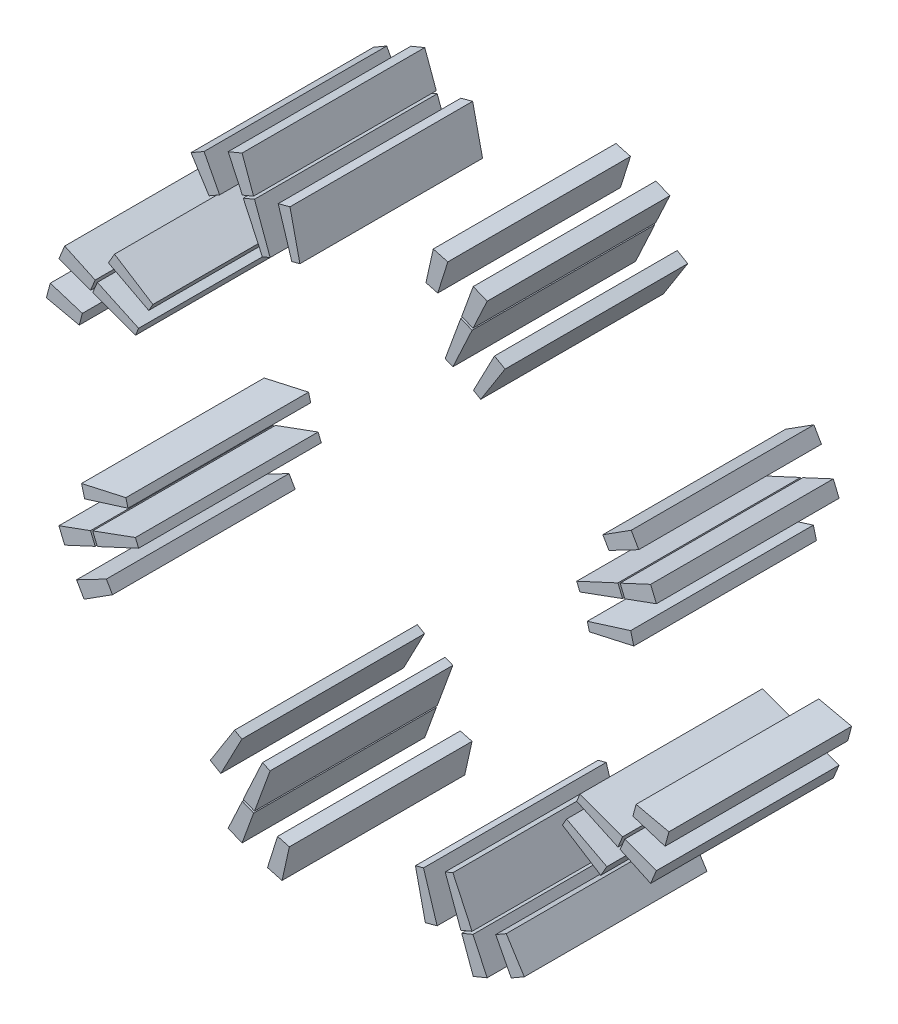
SolidWorks part; units mm, degrees
ref_plane "Спереди" through (0, 0, 0) normal (0, 0, 1) x (1, 0, 0)
ref_plane "Сверху" through (0, 0, 0) normal (0, 1, 0) x (1, 0, 0)
ref_plane "Справа" through (0, 0, 0) normal (1, 0, 0) x (0, 0, -1)
sketch "Эскиз1" plane through (0, 0, 0) normal (0, 0, 1) x (1, 0, 0)
  line L0 (38.0587, 9.486) -> (45.3455, 11.1141)
  line L1 (45.3455, 11.1141) -> (44.8274, 13.0476)
  line L2 (44.8274, 13.0476) -> (37.7028, 10.8142)
  line L3 (37.7028, 10.8142) -> (38.0587, 9.486)
  line L4 (43.8666, 17.0868) -> (49.0554, 18.98)
  line L5 (49.0554, 18.98) -> (48.1083, 21.2666)
  line L6 (48.1083, 21.2666) -> (43.1006, 18.9361)
  line L7 (43.1006, 18.9361) -> (43.8666, 17.0868)
  line L8 (36.4949, 14.3725) -> (43.5069, 16.9378)
  line L9 (43.5069, 16.9378) -> (42.7409, 18.7871)
  line L10 (42.7409, 18.7871) -> (35.9687, 15.6429)
  line L11 (35.9687, 15.6429) -> (36.4949, 14.3725)
  line L12 (41.261, 22.6664) -> (46.1584, 25.2206)
  line L13 (46.1584, 25.2206) -> (44.9209, 27.364)
  line L14 (44.9209, 27.364) -> (40.2602, 24.3999)
  line L15 (40.2602, 24.3999) -> (41.261, 22.6664)
  line L16 (20.2039, 33.6192) -> (24.2052, 39.923)
  line L17 (24.2052, 39.923) -> (22.4717, 40.9238)
  line L18 (22.4717, 40.9238) -> (19.0131, 34.3067)
  line L19 (19.0131, 34.3067) -> (20.2039, 33.6192)
  line L20 (18.9361, 43.1006) -> (21.2666, 48.1083)
  line L21 (21.2666, 48.1083) -> (18.98, 49.0554)
  line L22 (18.98, 49.0554) -> (17.0868, 43.8666)
  line L23 (17.0868, 43.8666) -> (18.9361, 43.1006)
  line L24 (15.6429, 35.9687) -> (18.7871, 42.7409)
  line L25 (18.7871, 42.7409) -> (16.9378, 43.5069)
  line L26 (16.9378, 43.5069) -> (14.3725, 36.4949)
  line L27 (14.3725, 36.4949) -> (15.6429, 35.9687)
  line L28 (13.1484, 45.2035) -> (14.8052, 50.4725)
  line L29 (14.8052, 50.4725) -> (12.4146, 51.1131)
  line L30 (12.4146, 51.1131) -> (11.2149, 45.7216)
  line L31 (11.2149, 45.7216) -> (13.1484, 45.2035)
  line L32 (-9.486, 38.0587) -> (-11.1141, 45.3455)
  line L33 (-11.1141, 45.3455) -> (-13.0476, 44.8274)
  line L34 (-13.0476, 44.8274) -> (-10.8142, 37.7028)
  line L35 (-10.8142, 37.7028) -> (-9.486, 38.0587)
  line L36 (-17.0868, 43.8666) -> (-18.98, 49.0554)
  line L37 (-18.98, 49.0554) -> (-21.2666, 48.1083)
  line L38 (-21.2666, 48.1083) -> (-18.9361, 43.1006)
  line L39 (-18.9361, 43.1006) -> (-17.0868, 43.8666)
  line L40 (-14.3725, 36.4949) -> (-16.9378, 43.5069)
  line L41 (-16.9378, 43.5069) -> (-18.7871, 42.7409)
  line L42 (-18.7871, 42.7409) -> (-15.6429, 35.9687)
  line L43 (-15.6429, 35.9687) -> (-14.3725, 36.4949)
  line L44 (-22.6664, 41.261) -> (-25.2206, 46.1584)
  line L45 (-25.2206, 46.1584) -> (-27.364, 44.9209)
  line L46 (-27.364, 44.9209) -> (-24.3999, 40.2602)
  line L47 (-24.3999, 40.2602) -> (-22.6664, 41.261)
  line L48 (-33.6192, 20.2039) -> (-39.923, 24.2052)
  line L49 (-39.923, 24.2052) -> (-40.9238, 22.4717)
  line L50 (-40.9238, 22.4717) -> (-34.3067, 19.0131)
  line L51 (-34.3067, 19.0131) -> (-33.6192, 20.2039)
  line L52 (-43.1006, 18.9361) -> (-48.1083, 21.2666)
  line L53 (-48.1083, 21.2666) -> (-49.0554, 18.98)
  line L54 (-49.0554, 18.98) -> (-43.8666, 17.0868)
  line L55 (-43.8666, 17.0868) -> (-43.1006, 18.9361)
  line L56 (-35.9687, 15.6429) -> (-42.7409, 18.7871)
  line L57 (-42.7409, 18.7871) -> (-43.5069, 16.9378)
  line L58 (-43.5069, 16.9378) -> (-36.4949, 14.3725)
  line L59 (-36.4949, 14.3725) -> (-35.9687, 15.6429)
  line L60 (-45.2035, 13.1484) -> (-50.4725, 14.8052)
  line L61 (-50.4725, 14.8052) -> (-51.1131, 12.4146)
  line L62 (-51.1131, 12.4146) -> (-45.7216, 11.2149)
  line L63 (-45.7216, 11.2149) -> (-45.2035, 13.1484)
  line L64 (-38.0587, -9.486) -> (-45.3455, -11.1141)
  line L65 (-45.3455, -11.1141) -> (-44.8274, -13.0476)
  line L66 (-44.8274, -13.0476) -> (-37.7028, -10.8142)
  line L67 (-37.7028, -10.8142) -> (-38.0587, -9.486)
  line L68 (-43.8666, -17.0868) -> (-49.0554, -18.98)
  line L69 (-49.0554, -18.98) -> (-48.1083, -21.2666)
  line L70 (-48.1083, -21.2666) -> (-43.1006, -18.9361)
  line L71 (-43.1006, -18.9361) -> (-43.8666, -17.0868)
  line L72 (-36.4949, -14.3725) -> (-43.5069, -16.9378)
  line L73 (-43.5069, -16.9378) -> (-42.7409, -18.7871)
  line L74 (-42.7409, -18.7871) -> (-35.9687, -15.6429)
  line L75 (-35.9687, -15.6429) -> (-36.4949, -14.3725)
  line L76 (-41.261, -22.6664) -> (-46.1584, -25.2206)
  line L77 (-46.1584, -25.2206) -> (-44.9209, -27.364)
  line L78 (-44.9209, -27.364) -> (-40.2602, -24.3999)
  line L79 (-40.2602, -24.3999) -> (-41.261, -22.6664)
  line L80 (-20.2039, -33.6192) -> (-24.2052, -39.923)
  line L81 (-24.2052, -39.923) -> (-22.4717, -40.9238)
  line L82 (-22.4717, -40.9238) -> (-19.0131, -34.3067)
  line L83 (-19.0131, -34.3067) -> (-20.2039, -33.6192)
  line L84 (-18.9361, -43.1006) -> (-21.2666, -48.1083)
  line L85 (-21.2666, -48.1083) -> (-18.98, -49.0554)
  line L86 (-18.98, -49.0554) -> (-17.0868, -43.8666)
  line L87 (-17.0868, -43.8666) -> (-18.9361, -43.1006)
  line L88 (-15.6429, -35.9687) -> (-18.7871, -42.7409)
  line L89 (-18.7871, -42.7409) -> (-16.9378, -43.5069)
  line L90 (-16.9378, -43.5069) -> (-14.3725, -36.4949)
  line L91 (-14.3725, -36.4949) -> (-15.6429, -35.9687)
  line L92 (-13.1484, -45.2035) -> (-14.8052, -50.4725)
  line L93 (-14.8052, -50.4725) -> (-12.4146, -51.1131)
  line L94 (-12.4146, -51.1131) -> (-11.2149, -45.7216)
  line L95 (-11.2149, -45.7216) -> (-13.1484, -45.2035)
  line L96 (9.486, -38.0587) -> (11.1141, -45.3455)
  line L97 (11.1141, -45.3455) -> (13.0476, -44.8274)
  line L98 (13.0476, -44.8274) -> (10.8142, -37.7028)
  line L99 (10.8142, -37.7028) -> (9.486, -38.0587)
  line L100 (17.0868, -43.8666) -> (18.98, -49.0554)
  line L101 (18.98, -49.0554) -> (21.2666, -48.1083)
  line L102 (21.2666, -48.1083) -> (18.9361, -43.1006)
  line L103 (18.9361, -43.1006) -> (17.0868, -43.8666)
  line L104 (14.3725, -36.4949) -> (16.9378, -43.5069)
  line L105 (16.9378, -43.5069) -> (18.7871, -42.7409)
  line L106 (18.7871, -42.7409) -> (15.6429, -35.9687)
  line L107 (15.6429, -35.9687) -> (14.3725, -36.4949)
  line L108 (22.6664, -41.261) -> (25.2206, -46.1584)
  line L109 (25.2206, -46.1584) -> (27.364, -44.9209)
  line L110 (27.364, -44.9209) -> (24.3999, -40.2602)
  line L111 (24.3999, -40.2602) -> (22.6664, -41.261)
  line L112 (33.6192, -20.2039) -> (39.923, -24.2052)
  line L113 (39.923, -24.2052) -> (40.9238, -22.4717)
  line L114 (40.9238, -22.4717) -> (34.3067, -19.0131)
  line L115 (34.3067, -19.0131) -> (33.6192, -20.2039)
  line L116 (43.1006, -18.9361) -> (48.1083, -21.2666)
  line L117 (48.1083, -21.2666) -> (49.0554, -18.98)
  line L118 (49.0554, -18.98) -> (43.8666, -17.0868)
  line L119 (43.8666, -17.0868) -> (43.1006, -18.9361)
  line L120 (35.9687, -15.6429) -> (42.7409, -18.7871)
  line L121 (42.7409, -18.7871) -> (43.5069, -16.9378)
  line L122 (43.5069, -16.9378) -> (36.4949, -14.3725)
  line L123 (36.4949, -14.3725) -> (35.9687, -15.6429)
  line L124 (45.2035, -13.1484) -> (50.4725, -14.8052)
  line L125 (50.4725, -14.8052) -> (51.1131, -12.4146)
  line L126 (51.1131, -12.4146) -> (45.7216, -11.2149)
  line L127 (45.7216, -11.2149) -> (45.2035, -13.1484)
extrude "Slot_copper_envelopes" add sketch "Эскиз1" along normal blind 30 from offset 15 separate body
